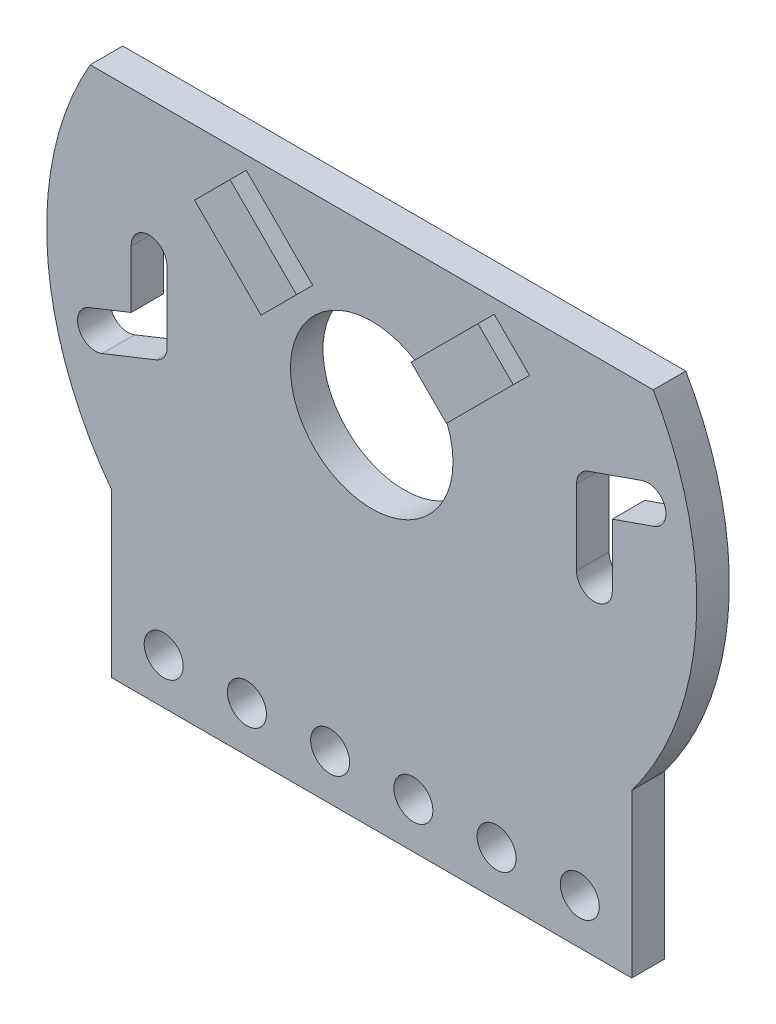
SolidWorks part; units mm, degrees
ref_plane "Plan de face" through (0, 0, 0) normal (0, 0, 1) x (1, 0, 0)
ref_plane "Plan de dessus" through (0, 0, 0) normal (0, 1, 0) x (1, 0, 0)
ref_plane "Plan de droite" through (0, 0, 0) normal (1, 0, 0) x (0, 0, -1)
sketch "Esquisse1" plane through (0, 0, 0) normal (0, 0, 1) x (1, 0, 0)
  line L0 (-9.5524, 0) -> (10.7605, 0) construction
  line L1 (0, 6.227) -> (0, -13.0879) construction
  line L2 (-8.3516, 5.5) -> (8.3516, 5.5)
  line L3 (-8, -6) -> (-8, -11)
  line L4 (-8, -11) -> (8, -11)
  line L5 (8, -11) -> (8, -6)
  line L6 (-10.7456, -9.6) -> (9.9861, -9.6) construction
  line L7 (-6.85, 0.8204) -> (-6.85, -1.3296) construction
  line L8 (-6.3, 0.8) -> (-6.3, -1.4442)
  line L9 (-7.4, 0.8) -> (-7.4, -0.9694)
  line L10 (-6.85, -1.3296) -> (-8.5, -2) construction
  line L11 (-6.642, -1.8514) -> (-8.293, -2.5096)
  line L12 (-7.4, -0.9694) -> (-8.707, -1.4904)
  line L13 (-5.7905, 0.8) -> (-7.65, 0.8) construction
  line L14 (6.85, 1.3154) -> (6.85, -1) construction
  line L15 (7.4, 1.3154) -> (7.4, -1)
  line L16 (6.3, 1.3154) -> (6.3, -1)
  line L17 (6.85, 1.3154) -> (11.27, 3.5613) construction
  line L18 (6.85, 2.2328) -> (6.85, -2.7816) construction
  line L19 (5.5719, 0.8) -> (8.2201, 0.8) construction
  line L23 (8.3839, 2.7117) -> (8.8822, 1.7311) construction
  circle A0 centre (0, 0) radius 2.5
  arc A1 (-8.3516, 5.5) -> (-8, -6) centre (0, 0) ccw
  arc A2 (8, -6) -> (8.3516, 5.5) centre (0, 0) ccw
  circle A3 centre (-6.4, -9.6) radius 0.6
  circle A4 centre (-3.84, -9.6) radius 0.6
  circle A5 centre (-1.28, -9.6) radius 0.6
  circle A6 centre (1.28, -9.6) radius 0.6
  circle A7 centre (3.84, -9.6) radius 0.6
  circle A8 centre (6.4, -9.6) radius 0.6
  arc A9 (-6.3, 0.8) -> (-7.4, 0.8) centre (-6.85, 0.8204) ccw
  arc A10 (7.4, 1.3154) -> (6.3, 1.3154) centre (6.85, 1.3154) ccw
  arc A11 (-6.642, -1.8514) -> (-6.3, -1.4442) centre (-6.85, -1.3296) ccw
  arc A12 (-8.707, -1.4904) -> (-8.293, -2.5096) centre (-8.5, -2) ccw
  arc A13 (6.3, -1) -> (7.4, -1) centre (6.85, -1) ccw
  point P17 (-8, -8.5)
  point P37 (-7.675, -1.6648)
  point P50 (6.85, 0.1577)
  dimension "D1" = 5
  dimension "D2" = 20
  dimension "D7" = 1.2
  dimension "D22" = 6.85
  dimension "D3" = 5.5
  dimension "D4" = 16
  dimension "D5" = 11
  dimension "D6" = 1.4
  dimension "D8" = 1.6
  dimension "D10" = 1.1
  dimension "D11" = 1.1
  dimension "D13" = 2.15
  dimension "D14" = 7.5
  dimension "D15" = 8.5
  dimension "D16" = 6.85
  dimension "D17" = 4.7
  dimension "D19" = 1.3154
  dimension "D20" = 1
  dimension "D23" = 1.1
  dimension "D9" = 6
extrude "Boss.-Extru.1" add sketch "Esquisse1" along normal blind 1
sketch "Esquisse2" plane through (0, 0, 1) normal (0, 0, 1) x (1, 0, 0)
  line L0 (6.85, 1.3154) -> (8.499, 1.8926) construction
  line L1 (6.6683, 1.8345) -> (8.3173, 2.4117)
  line L2 (7.0317, 0.7963) -> (8.6807, 1.3734)
  arc A0 (6.6683, 1.8345) -> (7.0317, 0.7963) centre (6.85, 1.3154) ccw
  arc A1 (8.6807, 1.3734) -> (8.3173, 2.4117) centre (8.499, 1.8926) ccw
  arc A2 (7.4, 1.3154) -> (6.3, 1.3154) centre (6.85, 1.3154) ccw construction
  point P2 (7.6745, 1.604)
  dimension "D1" = 1.1
extrude "Enlèv. mat.-Extru.1" cut sketch "Esquisse2" against normal through all
sketch "Esquisse3" plane through (0, 0, 1) normal (0, 0, 1) x (1, 0, 0)
  line L0 (-4.9508, 3.4988) -> (-2.9062, 1.4542)
  line L1 (-2.9062, 1.4542) -> (-1.8149, 2.5454)
  line L2 (-1.8149, 2.5454) -> (-3.8596, 4.5901)
  line L3 (-3.8596, 4.5901) -> (-4.9508, 3.4988)
extrude "Boss.-Extru.2" add sketch "Esquisse3" along normal blind 0.5
sketch "Esquisse4" plane through (0, 0, 1) normal (0, 0, 1) x (1, 0, 0)
  line L0 (1.7115, 2.511) -> (3.7677, 4.5671)
  line L1 (3.7677, 4.5671) -> (4.8532, 3.4816)
  line L2 (4.8532, 3.4816) -> (2.797, 1.4255)
  line L3 (2.797, 1.4255) -> (1.7115, 2.511)
extrude "Boss.-Extru.3" add sketch "Esquisse4" along normal blind 0.5
sketch "Croquis1" plane through (0, 0, 1) normal (0, 0, 1) x (1, 0, 0)
  line L0 (-8.6603, 5) -> (8.6603, 5)
  line L1 (-8.6603, 5) -> (-9.5765, 6.2874)
  line L2 (-9.5765, 6.2874) -> (9.5203, 6.0246)
  line L3 (9.5203, 6.0246) -> (8.6603, 5)
  arc A0 (-8.3516, 5.5) -> (-8, -6) centre (0, 0) ccw construction
  arc A1 (8, -6) -> (8.3516, 5.5) centre (0, 0) ccw construction
  dimension "D1" = 5
extrude "Cortar-Extruir1" cut sketch "Croquis1" against normal through all both and the other way through all
